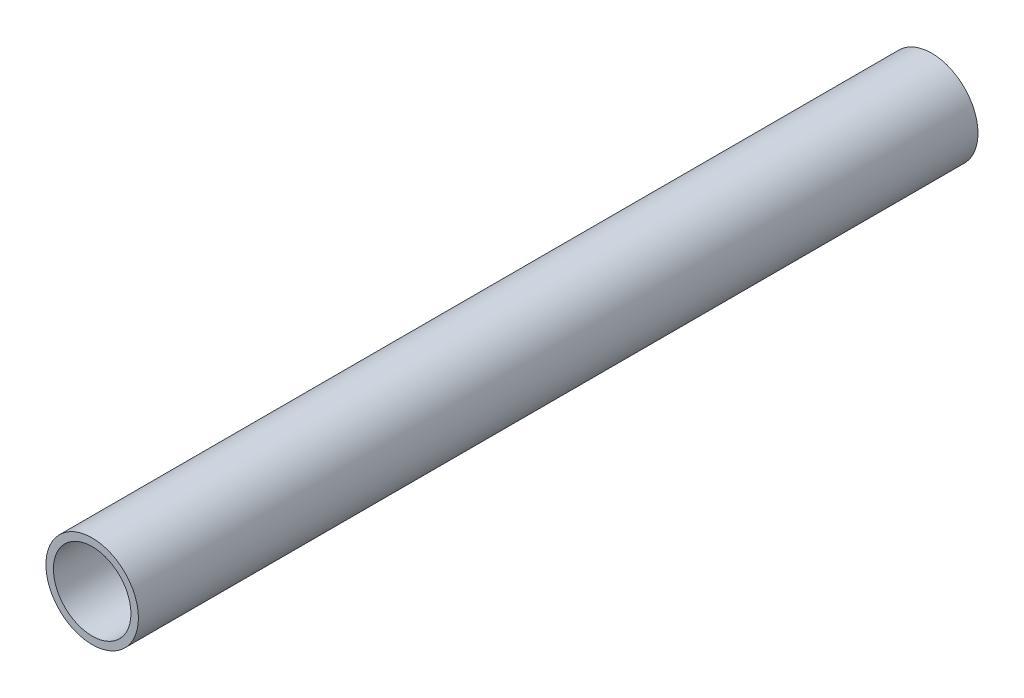
SolidWorks part; units mm, degrees
ref_plane "Front Plane" through (0, 0, 0) normal (0, 0, 1) x (1, 0, 0)
ref_plane "Top Plane" through (0, 0, 0) normal (0, 1, 0) x (1, 0, 0)
ref_plane "Right Plane" through (0, 0, 0) normal (1, 0, 0) x (0, 0, -1)
sketch "Sketch1" plane through (0, 0, 0) normal (0, 0, 1) x (1, 0, 0)
  circle A0 centre (0, 0) radius 30.3
  circle A1 centre (0, 0) radius 25.4
  dimension "D1" = 60.6
  dimension "D2" = 50.8
extrude "Boss-Extrude1" add sketch "Sketch1" along normal blind 550
